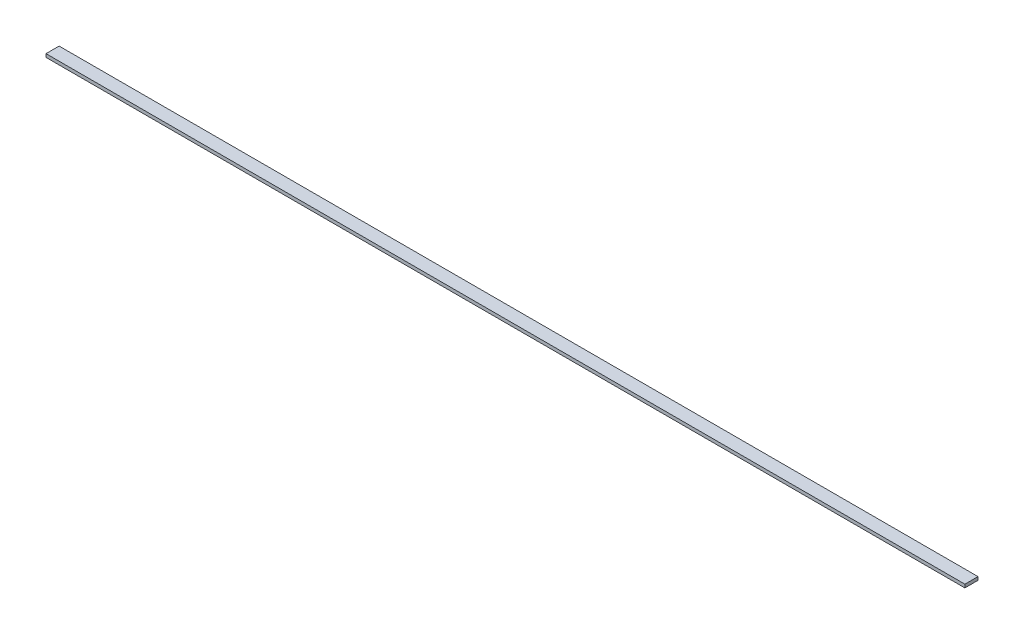
SolidWorks part; units mm, degrees
ref_plane "Front Plane" through (0, 0, 0) normal (0, 0, 1) x (1, 0, 0)
ref_plane "Top Plane" through (0, 0, 0) normal (0, 1, 0) x (1, 0, 0)
ref_plane "Right Plane" through (0, 0, 0) normal (1, 0, 0) x (0, 0, -1)
sketch "Sketch1" plane through (0, 0, 0) normal (0, 1, 0) x (1, 0, 0)
  line L1 (-889, -12.7) -> (889, -12.7)
  line L2 (-889, -12.7) -> (-889, 12.7)
  line L3 (-889, 12.7) -> (889, 12.7)
  line L4 (889, -12.7) -> (889, 12.7)
  line L5 (-889, -12.7) -> (889, 12.7) construction
  line L6 (-889, 12.7) -> (889, -12.7) construction
  point P0 (0, 0)
  dimension "D1" = 1778
  dimension "D2" = 25.4
extrude "Boss-Extrude1" add sketch "Sketch1" along normal blind 6.35
equation "\"horizontal-component-length\"= 70in'= \"railing-hypotenuse\" - \"railing-hypotenuse-horizontal-component-length-difference\""
equation "\"horizontal-component-width\"= 1in"
equation "\"D1@Sketch1\"=\"horizontal-component-length\""
equation "\"D2@Sketch1\"=\"horizontal-component-width\""
equation "\"material-thickness\"= .25in"
equation "\"D1@Boss-Extrude1\"=\"material-thickness\""
equation "\"railing-hypotenuse\"= 72in"
equation "\"railing-hypotenuse-horizontal-component-length-difference\"= 1.75in"
